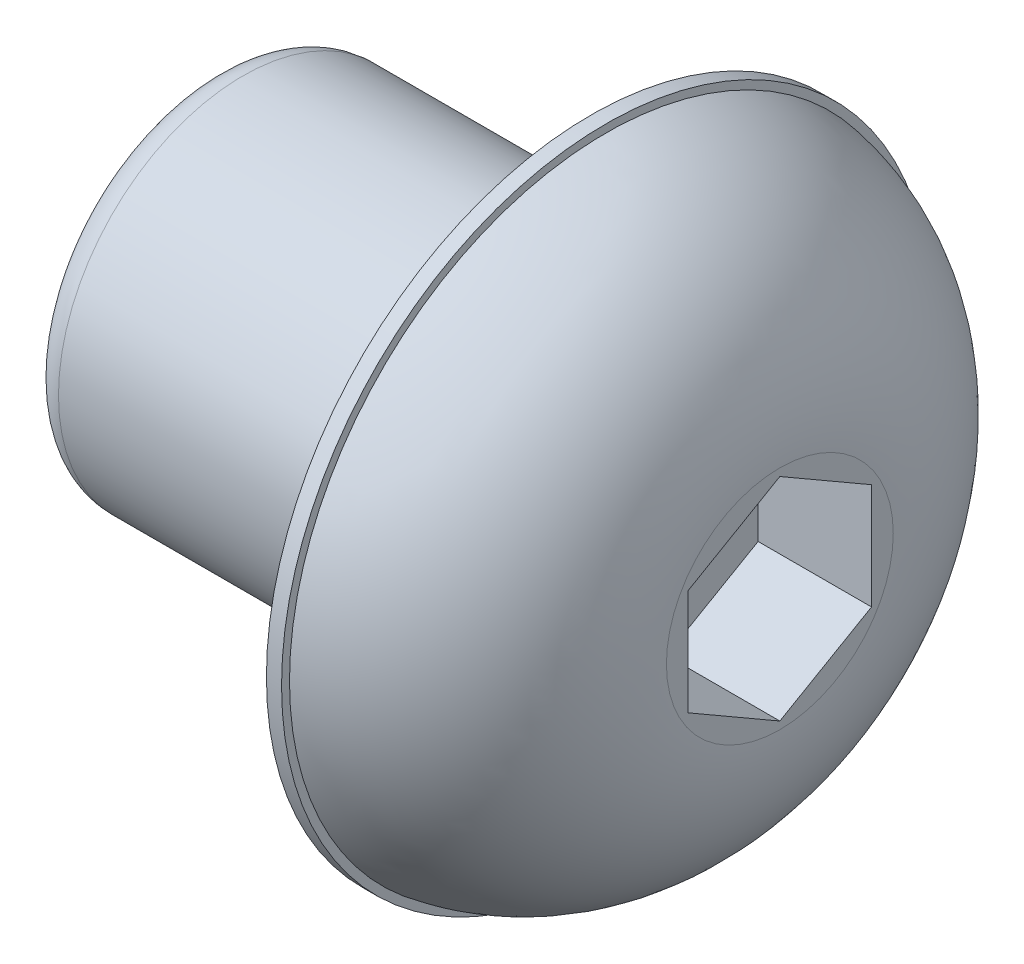
SolidWorks part; units mm, degrees
ref_plane "Front Plane" through (0, 0, 0) normal (0, 0, 1) x (1, 0, 0)
ref_plane "Top Plane" through (0, 0, 0) normal (0, 1, 0) x (1, 0, 0)
ref_plane "Right Plane" through (0, 0, 0) normal (1, 0, 0) x (0, 0, -1)
sketch "Sketch1" plane through (0, 0, 0) normal (0, 0, 1) x (1, 0, 0)
  line L0 (0, 0) -> (0, 6.1976)
  line L1 (0, 6.1976) -> (15.24, 6.1976)
  line L2 (0, 0) -> (12.7, 0)
  line L3 (12.7, 0) -> (12.7, -4.699)
  line L4 (12.7, -4.699) -> (13.208, -4.699)
  line L5 (13.208, -4.699) -> (13.208, -4.4323)
  line L6 (19.05, 2.3876) -> (15.24, 2.3876)
  line L7 (15.24, 2.3876) -> (15.24, 6.1976)
  arc A0 (19.05, 2.3876) -> (13.208, -4.4323) centre (12.1483, 2.3876) cw
  dimension "D1" = 12.7
  dimension "D2" = 6.1976
  dimension "D3" = 4.699
  dimension "D4" = 0.508
  dimension "D5" = 0.2667
  dimension "D6" = 3.81
  dimension "D7" = 3.81
  dimension "D8" = 6.35
revolve "Revolve1" add sketch "Sketch1" angle 360 about L1
sketch "Sketch2" plane through (15.24, 0, 0) normal (1, 0, 0) x (0, 0, -1)
  line L1 (0, 2.6414) -> (3.0797, 4.4195)
  line L2 (3.0797, 4.4195) -> (3.0798, 7.9757)
  line L3 (3.0798, 7.9757) -> (0, 9.7538)
  line L4 (0, 9.7538) -> (-3.0797, 7.9757)
  line L5 (-3.0797, 7.9757) -> (-3.0798, 4.4195)
  line L6 (-3.0798, 4.4195) -> (0, 2.6414)
  circle A0 centre (0, 6.1976) radius 3.0798 construction
  circle A1 centre (0, 6.1976) radius 3.81
  circle A2 centre (0, 6.1976) radius 3.81
  point P12 (3.0798, 6.1976)
  point P13 (-3.0798, 6.1976)
  dimension "D2" = 6.1595
  dimension "D1" = 0
extrude "Boss-Extrude1" add sketch "Sketch2" along normal blind 3.81
fillet "Fillet1" radius 1.016 1 edges at (0, 6.1976, 6.1976)
